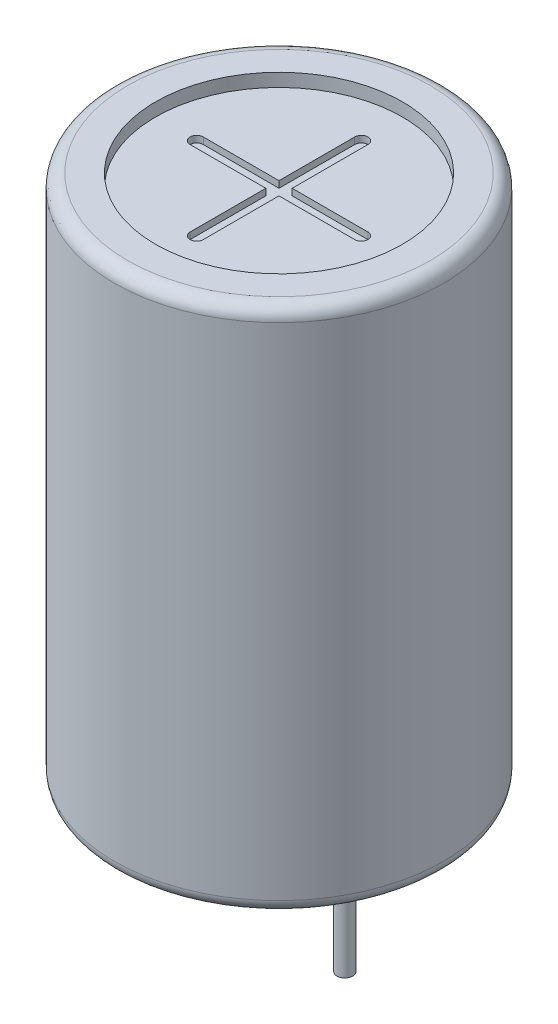
SolidWorks part; units mm, degrees
ref_plane "前视基准面" through (0, 0, 0) normal (0, 0, 1) x (1, 0, 0)
ref_plane "上视基准面" through (0, 0, 0) normal (0, 1, 0) x (1, 0, 0)
ref_plane "右视基准面" through (0, 0, 0) normal (1, 0, 0) x (0, 0, -1)
sketch "草图2" plane through (0, 0, 0) normal (0, 1, 0) x (1, 0, 0)
  circle A0 centre (0, 0) radius 6.25
  dimension "D1" = 12.5
extrude "凸台-拉伸1" add sketch "草图2" along normal blind 20 contours A0
fillet "圆角1" radius 0.5 2 edges at (0, 0, 6.25) (0, 20, 6.25)
sketch "草图3" plane through (0, 0, 0) normal (0, -1, 0) x (1, 0, 0)
  line L0 (-2.5, 0) -> (2.5, 0) construction
  circle A0 centre (-2.5, 0) radius 0.3
  circle A1 centre (2.5, 0) radius 0.3
  point P4 (0, 0)
  dimension "D2" = 0.6
  dimension "D3" = 0.6
  dimension "D1" = 5
extrude "凸台-拉伸2" add sketch "草图3" along normal blind 5
sketch "草图5" plane through (0, 20, 0) normal (0, 1, 0) x (1, 0, 0)
  circle A0 centre (0, 0) radius 4.6875
  dimension "D1" = 9.375
extrude "切除-拉伸1" cut sketch "草图5" against normal blind 1
sketch "草图6" plane through (0, 19, 0) normal (0, 1, 0) x (1, 0, 0)
  circle A0 centre (0, 0) radius 4.6875
  dimension "D1" = 9.375
extrude "凸台-拉伸3" add sketch "草图6" along normal blind 0.5
sketch "草图7" plane through (0, 19.5, 0) normal (0, 1, 0) x (1, 0, 0)
  line L0 (-3.125, 0) -> (3.125, 0) construction
  line L1 (-3.125, 0.25) -> (3.125, 0.25)
  line L2 (-3.125, -0.25) -> (3.125, -0.25)
  arc A0 (-3.125, 0.25) -> (-3.125, -0.25) centre (-3.125, 0) ccw
  arc A1 (3.125, -0.25) -> (3.125, 0.25) centre (3.125, 0) ccw
  point P2 (0, 0)
  dimension "D2" = 0.25
  dimension "D1" = 6.25
extrude "切除-拉伸2" cut sketch "草图7" against normal blind 0.25
sketch "草图8" plane through (0, 19.5, 0) normal (0, 1, 0) x (1, 0, 0)
  line L0 (0, -3.125) -> (0, 3.125) construction
  line L1 (-0.25, -3.125) -> (-0.25, 3.125)
  line L2 (0.25, -3.125) -> (0.25, 3.125)
  arc A0 (-0.25, -3.125) -> (0.25, -3.125) centre (0, -3.125) ccw
  arc A1 (0.25, 3.125) -> (-0.25, 3.125) centre (0, 3.125) ccw
  point P2 (0, 0)
  dimension "D2" = 0.25
  dimension "D1" = 6.25
extrude "切除-拉伸3" cut sketch "草图8" against normal blind 0.25
equation "\"R\" = 12.5'直径"
equation "\"D1@草图2\"=\"R\""
equation "\"H\" = 20'高度"
equation "\"M\" = 5'引脚间距"
equation "\"P\"= 0.6'引脚直径"
equation "\"D1@凸台-拉伸1\"=\"H\""
equation "\"D2@草图3\"=\"P\""
equation "\"D3@草图3\"=\"P\""
equation "\"D1@草图3\"=\"M\""
equation "\"L\"= 5'引脚长度"
equation "\"D1@凸台-拉伸2\"=\"L\""
equation "\"D1@草图5\"=\"R\"*3/4"
equation "\"D1@草图7\"=\"R\"/2"
equation "\"D1@草图8\"=\"R\"/2"
equation "\"D1@草图6\"=\"R\"*3/4"
